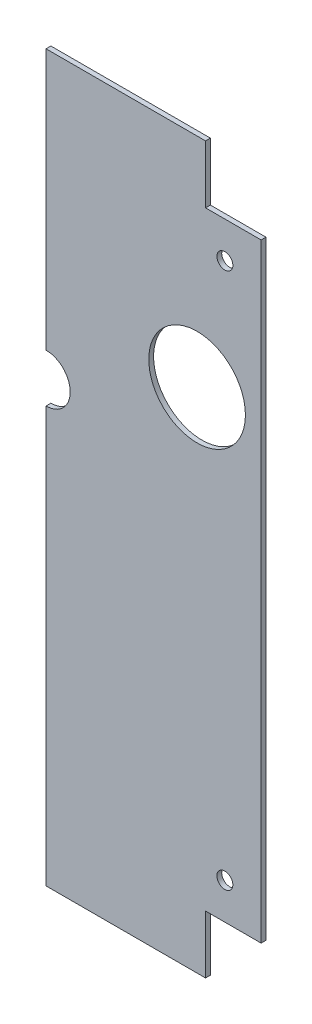
SolidWorks part; units mm, degrees
ref_plane "Ebene vorne" through (0, 0, 0) normal (0, 0, 1) x (1, 0, 0)
ref_plane "Ebene oben" through (0, 0, 0) normal (0, 1, 0) x (1, 0, 0)
ref_plane "Ebene rechts" through (0, 0, 0) normal (1, 0, 0) x (0, 0, -1)
sketch "Skizze1" plane through (0, 0, 0) normal (0, 0, 1) x (1, 0, 0)
  line L0 (-4.0015, -24.0098) -> (-27.0015, -24.0098)
  line L2 (-4.0015, -24.0098) -> (-4.0015, -276.0098)
  line L5 (-27.0015, -24.0098) -> (-27.0015, -0.0098)
  line L6 (-27.0015, -0.0098) -> (-93.0015, -0.0098)
  line L8 (-93.0015, -300.0098) -> (-27.0015, -300.0098)
  line L9 (-27.0015, -300.0098) -> (-27.0015, -276.0098)
  line L10 (-27.0015, -276.0098) -> (-4.0015, -276.0098)
  line L12 (-93.0015, -0.0098) -> (-93.0015, -300.0098)
  dimension "D6" = 24
  dimension "D7" = 23
  dimension "D1" = 300
  dimension "D3" = 23
  dimension "D4" = 66
  dimension "D5" = 24
  dimension "D8" = 66
ref_plane "Ebene1" through (-3, -22.9291, 1) normal (0, -1, 0) x (-1, 0, 0)
extrude "Aufsatz-Linear austragen1" add sketch "Skizze1" along normal blind 2 contours L8 L9 L10 L2 L0 L5 L6 L12
sketch "Skizze2" plane through (0, 0, 2) normal (0, 0, 1) x (1, 0, 0)
  line L0 (-93.0015, 0.0709) -> (-93.0015, -299.9291) construction
  line L2 (-93.0015, -300.0098) -> (-27.0015, -300.0098) construction
  circle A3 centre (-30.5, -90.0098) radius 20
  circle A4 centre (-93.0015, -118.0098) radius 10
  dimension "D1" = 20
  dimension "D3" = 210
  dimension "D2" = 182
extrude "Schnitt-Linear austragen1" cut sketch "Skizze2" against normal blind 10
hole_wizard "Durchgangsloch für M61" positions "Skizze3" profile "Skizze4" hole size "M6" standard "DIN" end condition through all
sketch "Skizze3" plane through (0, 0, 2) normal (0, 0, 1) x (1, 0, 0)
  line L0 (-4.0015, -24.0098) -> (-4.0015, -276.0098) construction
  line L3 (-27.0015, -276.0098) -> (-4.0015, -276.0098) construction
  line L7 (-4.0015, -24.0098) -> (-27.0015, -24.0098) construction
  point P0 (-19.0015, -39.0098)
  point P2 (-19.0015, -261.0098)
  dimension "D1" = 15
  dimension "D2" = 15
  dimension "D3" = 15
  dimension "D4" = 15
sketch "Skizze4" plane through (-19.0015, -39.0098, 2) normal (1, 0, 0) x (0, -1, 0)
  line L0 (0, 0) -> (0, 2)
  line L1 (0, 2) -> (3.3, 2)
  line L2 (3.3, 2) -> (3.3, 0)
  line L5 (3.3, 0) -> (0, 0)
  line L11 (0, -6.35) -> (0, 107.95) construction
  dimension "Bohrerdurchmesser" = 6.6
  dimension "Bohrungstiefe" = 2
